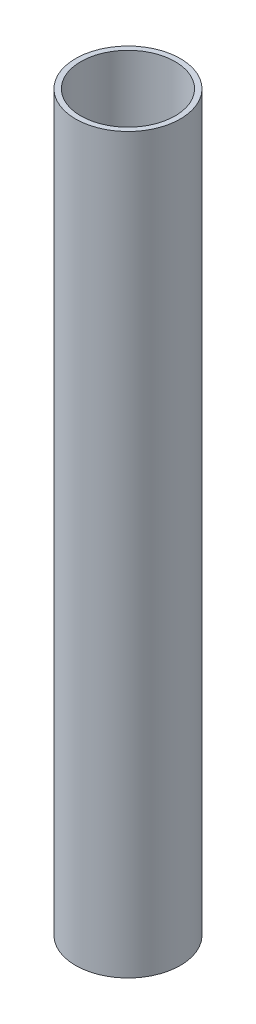
SolidWorks part; units mm, degrees
material "Chrome Stainless Steel"
ref_plane "Front Plane" through (0, 0, 0) normal (0, 0, 1) x (1, 0, 0)
ref_plane "Top Plane" through (0, 0, 0) normal (0, 1, 0) x (1, 0, 0)
ref_plane "Right Plane" through (0, 0, 0) normal (1, 0, 0) x (0, 0, -1)
sketch "Sketch1" plane through (0, 0, 0) normal (0, 1, 0) x (1, 0, 0)
  circle A0 centre (0, 0) radius 1.27
  circle A1 centre (0, 0) radius 1.143
  dimension "D1" = 2.286
  dimension "D2" = 2.54
extrude "Boss-Extrude1" add sketch "Sketch1" along normal blind 17.78
